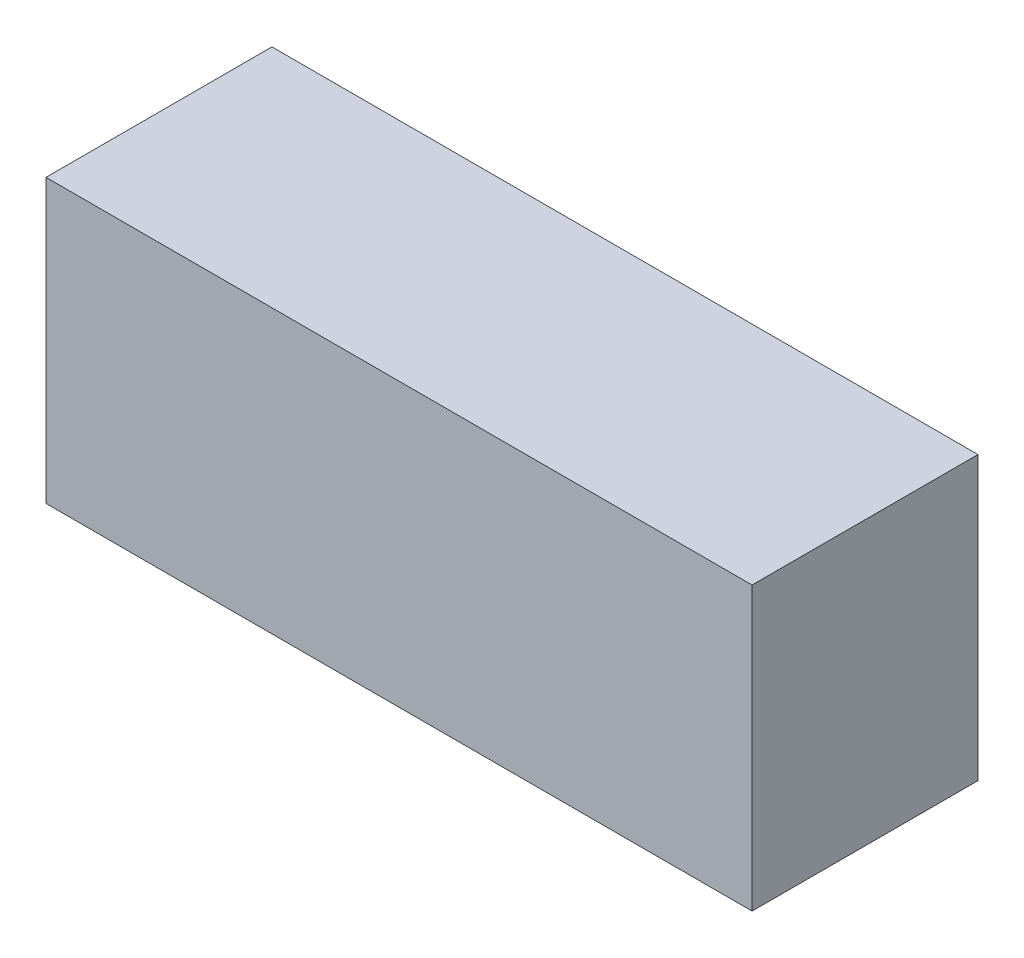
SolidWorks part; units mm, degrees
material "Бетон"
ref_plane "Спереди" through (0, 0, 0) normal (0, 0, 1) x (1, 0, 0)
ref_plane "Сверху" through (0, 0, 0) normal (0, 1, 0) x (1, 0, 0)
ref_plane "Справа" through (0, 0, 0) normal (1, 0, 0) x (0, 0, -1)
sketch "Эскиз1" plane through (0, 0, 0) normal (0, 1, 0) x (1, 0, 0)
  line L1 (0, 0) -> (625, 0)
  line L2 (0, 0) -> (0, 200)
  line L3 (0, 200) -> (625, 200)
  line L4 (625, 0) -> (625, 200)
  dimension "D1" = 625
  dimension "D2" = 200
extrude "Бобышка-Вытянуть1" add sketch "Эскиз1" along normal blind 250
